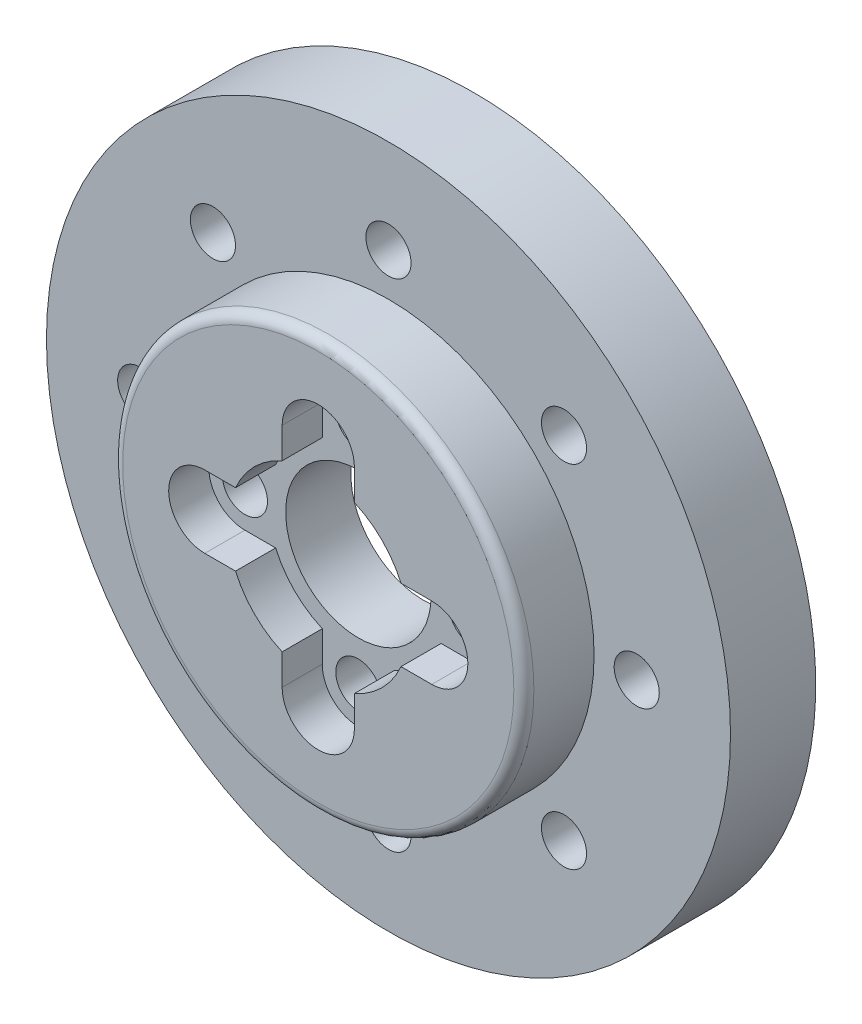
SolidWorks part; units mm, degrees
ref_plane "Front Plane" through (0, 0, 0) normal (0, 0, 1) x (1, 0, 0)
ref_plane "Top Plane" through (0, 0, 0) normal (0, 1, 0) x (1, 0, 0)
ref_plane "Right Plane" through (0, 0, 0) normal (1, 0, 0) x (0, 0, -1)
sketch "Sketch1" plane through (0, 0, 0) normal (0, 0, 1) x (1, 0, 0)
  circle A0 centre (0, 0) radius 34.1
  dimension "D1" = 68.2
extrude "Boss-Extrude1" add sketch "Sketch1" along normal mid plane 3.5
sketch "Sketch4" plane through (0, 0, 1.75) normal (0, 0, 1) x (1, 0, 0)
  circle A0 centre (0, 0) radius 28.5
  dimension "D1" = 57
extrude "Boss-Extrude2" add sketch "Sketch4" along normal blind 2
sketch "Sketch5" plane through (0, 0, -1.75) normal (0, 0, -1) x (-1, 0, 0)
  circle A0 centre (0, 0) radius 16.25
  circle A1 centre (0, 0) radius 34.1 construction
  circle A2 centre (0, 0) radius 34.1
  dimension "D1" = 32.5
extrude "Boss-Extrude3" add sketch "Sketch5" along normal blind 5
sketch "Sketch3" plane through (0, 0, 1.75) normal (0, 0, 1) x (1, 0, 0)
  circle A8 centre (0, 0) radius 11.3137 construction
  circle A9 centre (0, 11.3137) radius 2.25
  circle A11 centre (11.3137, 0) radius 2.25
  circle A13 centre (0, -11.3137) radius 2.25
  circle A15 centre (-11.3137, 0) radius 2.25
  point P21 (0, 0)
  dimension "D3" = 22.6274
  dimension "D4" = 4.5
  dimension "D5" = 4
extrude "Cut-Extrude2" cut sketch "Sketch3" against normal through all both and the other way through all
sketch "Sketch2" plane through (0, 0, 1.75) normal (0, 0, 1) x (1, 0, 0)
  circle A0 centre (0, 0) radius 7.25
  dimension "D1" = 14.5
extrude "Cut-Extrude1" cut sketch "Sketch2" along normal through all both and the other way through all
sketch "Sketch6" plane through (0, 0, 3.75) normal (0, 0, 1) x (1, 0, 0)
  circle A0 centre (0, 24.75) radius 2.25
  dimension "D1" = 4.5
  dimension "D2" = 24.75
extrude "Cut-Extrude3" cut sketch "Sketch6" against normal through all both and the other way through all
pattern_circular "CirPattern1" count 8 over 360 about axis through (0, 0, 0) along (0, 0, 1) of "Cut-Extrude3"
sketch "Sketch7" plane through (0, 0, 3.75) normal (0, 0, 1) x (1, 0, 0)
  circle A0 centre (0, 0) radius 20.5
  circle A5 centre (0, -11.3137) radius 2.25 construction
  circle A6 centre (11.3137, 0) radius 2.25 construction
  circle A7 centre (0, 11.3137) radius 2.25 construction
  circle A8 centre (-11.3137, 0) radius 2.25 construction
  circle A9 centre (0, 0) radius 7.25 construction
  circle A10 centre (0, -11.3137) radius 2.25
  circle A11 centre (11.3137, 0) radius 2.25
  circle A12 centre (0, 11.3137) radius 2.25
  circle A13 centre (-11.3137, 0) radius 2.25
  circle A14 centre (0, 0) radius 7.25
  dimension "D1" = 41
extrude "Boss-Extrude4" add sketch "Sketch7" along normal blind 5
sketch "Sketch8" plane through (0, 0, 1.75) normal (0, 0, 1) x (1, 0, 0)
  circle A0 centre (0, 0) radius 28.5 construction
  circle A1 centre (0, 0) radius 34.1
  circle A2 centre (0, 0) radius 34.1
  circle A3 centre (0, 0) radius 28.5
  dimension "D1" = 0
extrude "Boss-Extrude5" add sketch "Sketch8" along normal up to surface (2 mm away) up to face at (20.5, 0, 3.75)
sketch "Sketch10" plane through (0, 0, 3.75) normal (0, 0, 1) x (1, 0, 0)
  circle A0 centre (0, 0) radius 20.5 construction
  circle A1 centre (0, 0) radius 34.1
  circle A2 centre (0, 0) radius 34.1
  circle A3 centre (0, 0) radius 20.5
  dimension "D1" = 0
extrude "Cut-Extrude4" cut sketch "Sketch10" against normal blind 2
sketch "Sketch11" plane through (0, 0, 8.75) normal (0, 0, 1) x (1, 0, 0)
  line L0 (-11.3137, 3.6) -> (-8.2486, 3.6)
  line L1 (-3.6, 8.2486) -> (-3.6, 11.3137)
  line L2 (3.6, 11.3137) -> (3.6, 8.2486)
  line L3 (8.2486, 3.6) -> (11.3137, 3.6)
  line L4 (11.3137, -3.6) -> (8.2486, -3.6)
  line L5 (3.6, -8.2486) -> (3.6, -11.3137)
  line L6 (-3.6, -11.3137) -> (-3.6, -8.2486)
  line L7 (-8.2486, -3.6) -> (-11.3137, -3.6)
  circle A0 centre (-11.3137, 0) radius 2.25 construction
  circle A1 centre (0, -11.3137) radius 2.25 construction
  circle A2 centre (11.3137, 0) radius 2.25 construction
  circle A3 centre (0, 11.3137) radius 2.25 construction
  circle A4 centre (-11.3137, 0) radius 2.25 construction
  circle A5 centre (0, -11.3137) radius 2.25 construction
  circle A6 centre (11.3137, 0) radius 2.25 construction
  circle A7 centre (0, 11.3137) radius 2.25 construction
  arc A8 (-3.6, -11.3137) -> (3.6, -11.3137) centre (0, -11.3137) ccw
  arc A9 (11.3137, -3.6) -> (11.3137, 3.6) centre (11.3137, 0) ccw
  arc A10 (3.6, 11.3137) -> (-3.6, 11.3137) centre (0, 11.3137) ccw
  arc A11 (-11.3137, 3.6) -> (-11.3137, -3.6) centre (-11.3137, 0) ccw
  arc A12 (-8.2486, -3.6) -> (-3.6, -8.2486) centre (0, 0) ccw
  arc A13 (-3.6, 8.2486) -> (-8.2486, 3.6) centre (0, 0) ccw
  arc A14 (8.2486, 3.6) -> (3.6, 8.2486) centre (0, 0) ccw
  arc A15 (3.6, -8.2486) -> (8.2486, -3.6) centre (0, 0) ccw
  dimension "D1" = 7.2
  dimension "D2" = 18
extrude "Cut-Extrude5" cut sketch "Sketch11" against normal blind 4
sketch "Sketch12" plane through (0, 0, -6.75) normal (0, 0, -1) x (-1, 0, 0)
  circle A0 centre (0, 24.75) radius 4.6
  circle A1 centre (17.5009, 17.5009) radius 4.6
  circle A2 centre (24.75, 0) radius 4.6
  circle A3 centre (17.5009, -17.5009) radius 4.6
  circle A4 centre (0, -24.75) radius 4.6
  circle A5 centre (-17.5009, -17.5009) radius 4.6
  circle A6 centre (-24.75, 0) radius 4.6
  circle A7 centre (-17.5009, 17.5009) radius 4.6
  point P19 (0, 0)
  dimension "D1" = 9.2
  dimension "D2" = 8
extrude "Cut-Extrude6" cut sketch "Sketch12" against normal blind 3
fillet "Fillet2" radius 1 1 edges at (20.5, 0, 8.75)
fillet "Fillet3" radius 1 1 edges at (-16.25, 0, -1.75)
